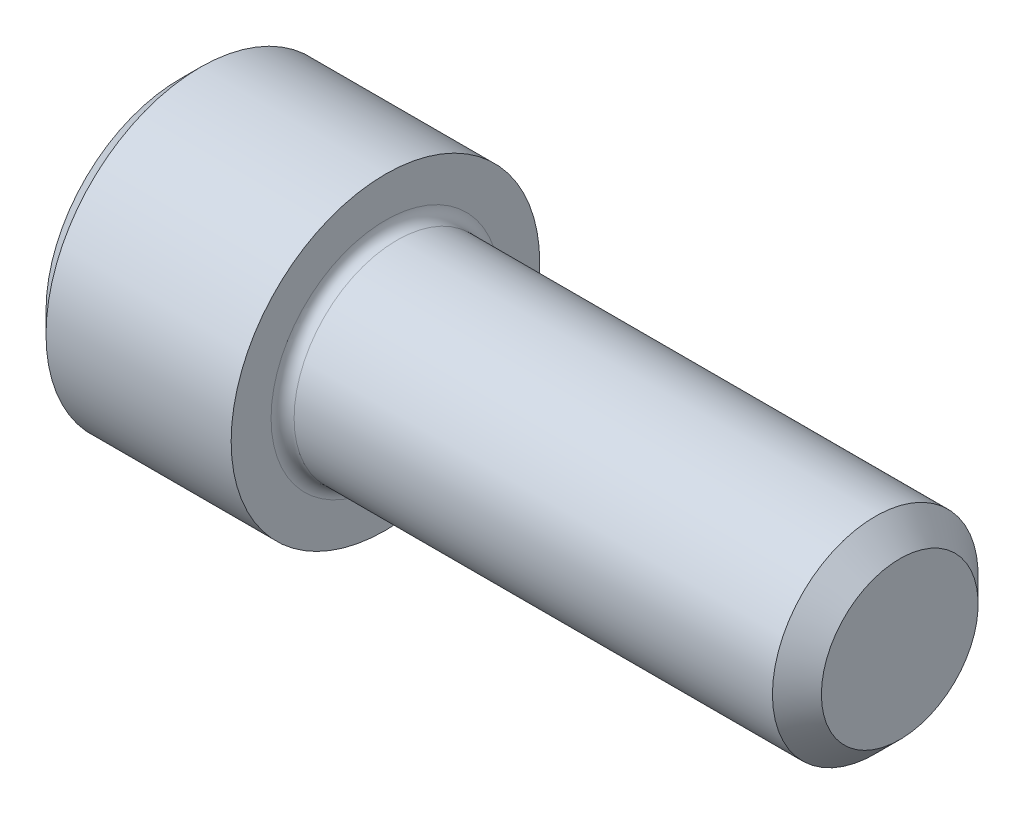
SolidWorks part; units mm, degrees
revolve "Base-Revolve" add sketch "BodySke"
sketch "BodySke" plane through (0, 0, 0) normal (0, 0, 1) x (1, 0, 0)
  line L0 (0, 0) -> (0, 4.1275)
  line L1 (0.635, 4.7625) -> (6.35, 4.7625)
  line L2 (6.35, 4.7625) -> (6.35, 3.175)
  line L3 (6.35, 3.175) -> (21.4693, 3.175)
  line L4 (22.225, 2.4193) -> (22.225, 0)
  line L5 (22.225, 0) -> (0, 0)
  line L6 (-31.75, 0) -> (127, 0) construction
  line L7 (0, 4.1275) -> (0.635, 4.7625)
  line L8 (22.225, 2.4193) -> (21.4693, 3.175)
  line L9 (0, -4.1275) -> (0.635, -4.7625) construction
  line L10 (22.225, -2.4193) -> (21.4694, -3.175) construction
  line L11 (7.62, 9.525) -> (7.62, 3.175) construction
  line L12 (6.35, 9.525) -> (6.35, 3.175) construction
  line L13 (-15.875, 9.525) -> (-15.875, 3.175) construction
  dimension "Diameter" = 6.35
  dimension "Head_ht" = 6.35
  dimension "Length" = 15.875
  dimension "Body_ch_ang" = 45
  dimension "Head_dia" = 9.525
  dimension "Head_ch_ang" = 45
  dimension "Head_side_ht" = 5.715
  dimension "Minor_dia" = 4.8387
  dimension "Advance" = 1.27
  dimension "Thread_nom" = 15.875
  dimension "Thread_length" = 38.1
cosmetic thread "ThreadCosmetic" [suppressed]
fillet "Fillet1" radius 0.3556 1 edges at (6.35, 0, 3.175)
ref_plane "Plane1" through (0, 0, 0) normal (0, 0, 1) x (1, 0, 0)
ref_plane "Plane2" through (0, 0, 0) normal (0, 1, 0) x (1, 0, 0)
ref_plane "Plane3" through (0, 0, 0) normal (1, 0, 0) x (0, 0, -1)
sketch "Sketch2" plane through (0, 0, 0) normal (0, 0, 1) x (1, 0, 0)
  line L0 (0, 2.3813) -> (3.048, 2.3813)
  line L1 (3.048, 2.3813) -> (4.4228, 0)
  line L2 (-31.75, 0) -> (127, 0) construction
  line L3 (4.4228, 0) -> (0, 0)
  line L4 (0, 0) -> (0, 2.3813)
  line L5 (0, 4.1275) -> (0, -4.1275) construction
  line L6 (0, 0) -> (47.625, 0) construction
  line L7 (6.35, -4.7625) -> (6.35, 4.7625) construction
  dimension "D1" = 2.3813
  dimension "D2" = 60
revolve "Hex-PreBroach" cut sketch "Sketch2" angle 360 about L6
sketch "Sketch3" plane through (0, 0, 0) normal (-1, 0, 0) x (0, 0.5, 0.866)
  line L0 (1.3748, 2.3813) -> (-1.3748, 2.3813)
  line L1 (-1.3748, 2.3813) -> (-2.7496, 0)
  line L2 (1.3748, 2.3813) -> (2.7496, 0)
  line L3 (1.3748, -2.3813) -> (2.7496, 0)
  line L4 (1.3748, -2.3813) -> (-1.3748, -2.3813)
  line L5 (-1.3748, -2.3813) -> (-2.7496, 0)
  dimension "D1" = 2.3813
  dimension "D2" = 2.3813
  dimension "Hex_size" = 4.7625
extrude "Hex" cut sketch "Sketch3" against normal blind 3.048
sketch "Sketch4" plane through (0, 0, 0) normal (-1, 0, 0) x (0, 0, 1)
  line L0 (0, 0) -> (2.8067, 0)
  line L1 (0, 0) -> (6.1484, 3.5498) construction
  line L2 (0, 0) -> (1.4033, 2.4307)
  line L3 (2.3336, 0.614) -> (2.6851, 0.817)
  line L4 (1.6986, 1.7139) -> (2.0501, 1.9169)
  arc A0 (2.3336, 0.614) -> (1.6986, 1.7139) centre (0, 0) ccw
  arc A1 (2.8067, 0) -> (2.6851, 0.817) centre (0, 0) ccw
  arc A2 (1.4033, 2.4307) -> (2.0501, 1.9169) centre (0, 0) cw
  dimension "D1" = 30
  dimension "D2" = 60
  dimension "Spline_p_dim" = 1.27
  dimension "D3" = 0.635
extrude "Spline" [suppressed] cut sketch "Sketch4" against normal blind 3.048
pattern_circular "CirPattern1" [suppressed] count 6 every 60
sketch "Sketch5" plane through (0, 0, 0) normal (0, 0, 1) x (1, 0, 0)
  line L0 (-31.75, 0) -> (127, 0) construction
  line L2 (0, 4.1275) -> (0, -4.1275) construction
  circle A0 centre (2.159, 0) radius 0.5905
  dimension "Drilled_hole_dia" = 1.1811
  dimension "Drilled_hole_loc" = 2.159
extrude "Hole" [suppressed] cut sketch "Sketch5" against normal through all and the other way through all
pattern_circular "Drilled-4" [suppressed] count 2 every 60
pattern_circular "Drilled-6" [suppressed] count 3 every 60
sketch "ThdSchSke" plane through (0, 0, 0) normal (0, 0, 1) x (1, 0, 0)
  line L0 (7.62, -2.4193) -> (7.0909, -3.175)
  line L1 (7.62, -2.4193) -> (8.1491, -3.175)
  line L2 (8.1491, -3.175) -> (8.1491, -3.9688)
  line L3 (-3.175, 0) -> (5.1513, 0) construction
  line L5 (8.1491, -3.9688) -> (7.0909, -3.9688)
  line L6 (7.0909, -3.9688) -> (7.0909, -3.175)
  line L7 (0, 4.1275) -> (0, -4.1275) construction
  dimension "Thread_minor" = 4.8387
  dimension "Diameter" = 6.35
  dimension "Start" = 7.62
revolve "ThreadSchematic" [suppressed] cut sketch "ThdSchSke" angle 360 about L3
pattern_linear "ThdSchPat" [suppressed]
equation "\"D2@Sketch3\" = \"Hex_size@Sketch3\" / 2"
equation "\"D1@Sketch3\" = \"Hex_size@Sketch3\" / 2"
equation "\"D1@Sketch2\" = \"Hex_size@Sketch3\" / 2"
equation "\"D3@Sketch4\" = \"Spline_p_dim@Sketch4\" / 2"
equation "\"Thread_minor@ThreadCosmetic\"  =  \"Minor_dia@BodySke\""
equation "\"D2@CirPattern1\" = 360 / \"Num_teeth@CirPattern1\""
equation "\"Wall_thickness@Sketch2\" = \"Head_ht@BodySke\" - \"Key_eng@Hex\""
equation "\"Thread_length@ThreadCosmetic\" = ((sgn( (\"Length@BodySke\" - \"Advance@BodySke\" ) - \"Thread_nom@BodySke\" )-1)*( (\"Length@BodySke\" - \"Advance@BodySke\" ) - \"Thread_nom@BodySke\" ))/-2+ \"Thread_nom@BodySke\""
equation "\"Thread_minor@ThdSchSke\" = \"Minor_dia@BodySke\""
equation "\"Diameter@ThdSchSke\" = \"Diameter@BodySke\""
equation "\"Overcut@ThdSchSke\" = \"Diameter@BodySke\" * 1.25"
equation "\"Start@ThdSchSke\" = \"Head_ht@BodySke\" + \"Length@BodySke\" - \"Thread_length@ThreadCosmetic\"  '---Non-countersunk---"
equation "\"Num_threads@ThdSchPat\" = int( \"Thread_length@ThreadCosmetic\" / \"Advance@BodySke\" + 0.999 )  + 1"
equation "\"Advance@ThdSchPat\" = \"Thread_length@ThreadCosmetic\" /  (\"Num_threads@ThdSchPat\" - 1) 'relax it"
equation "\"Num_threads@ThdSchPat\" = \"Num_threads@ThdSchPat\" - sgn( \"Num_threads@ThdSchPat\" - 1) '---chamfered tips only---"
